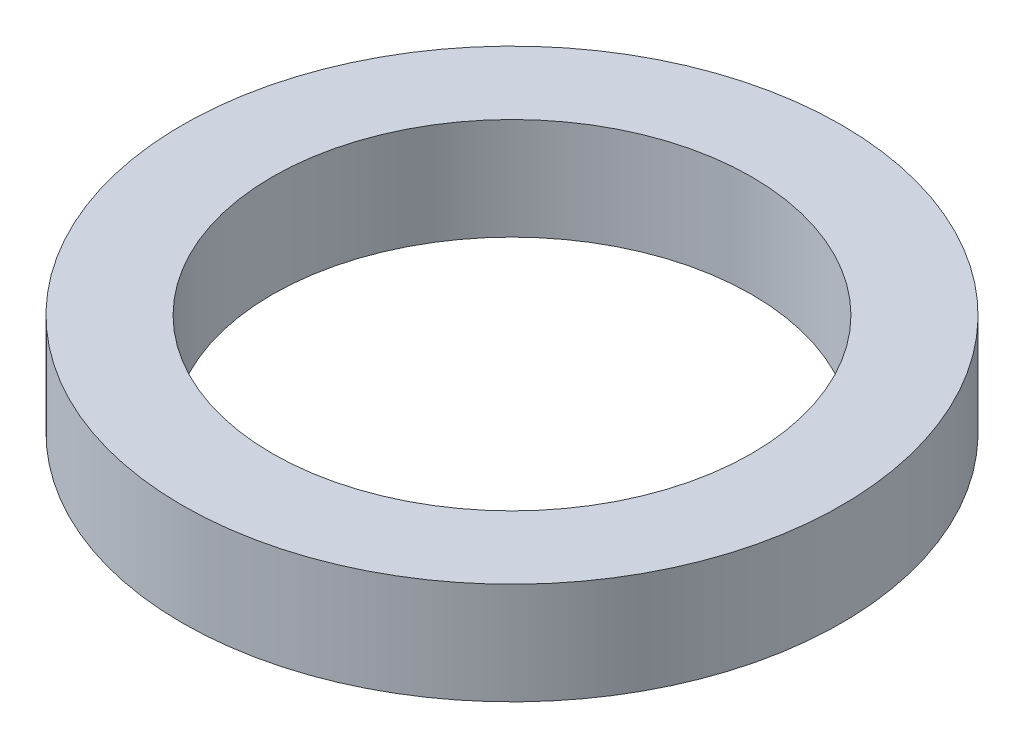
SolidWorks part; units mm, degrees
ref_plane "前视基准面" through (0, 0, 0) normal (0, 0, 1) x (1, 0, 0)
ref_plane "上视基准面" through (0, 0, 0) normal (0, 1, 0) x (1, 0, 0)
ref_plane "右视基准面" through (0, 0, 0) normal (1, 0, 0) x (0, 0, -1)
sketch "草图1" plane through (0, 0, 0) normal (0, 1, 0) x (1, 0, 0)
  circle A0 centre (0, 0) radius 4
  circle A1 centre (0, 0) radius 5.5
  dimension "D1" = 1.5
  dimension "D2" = 11
extrude "凸台-拉伸1" add sketch "草图1" along normal blind 1.7
